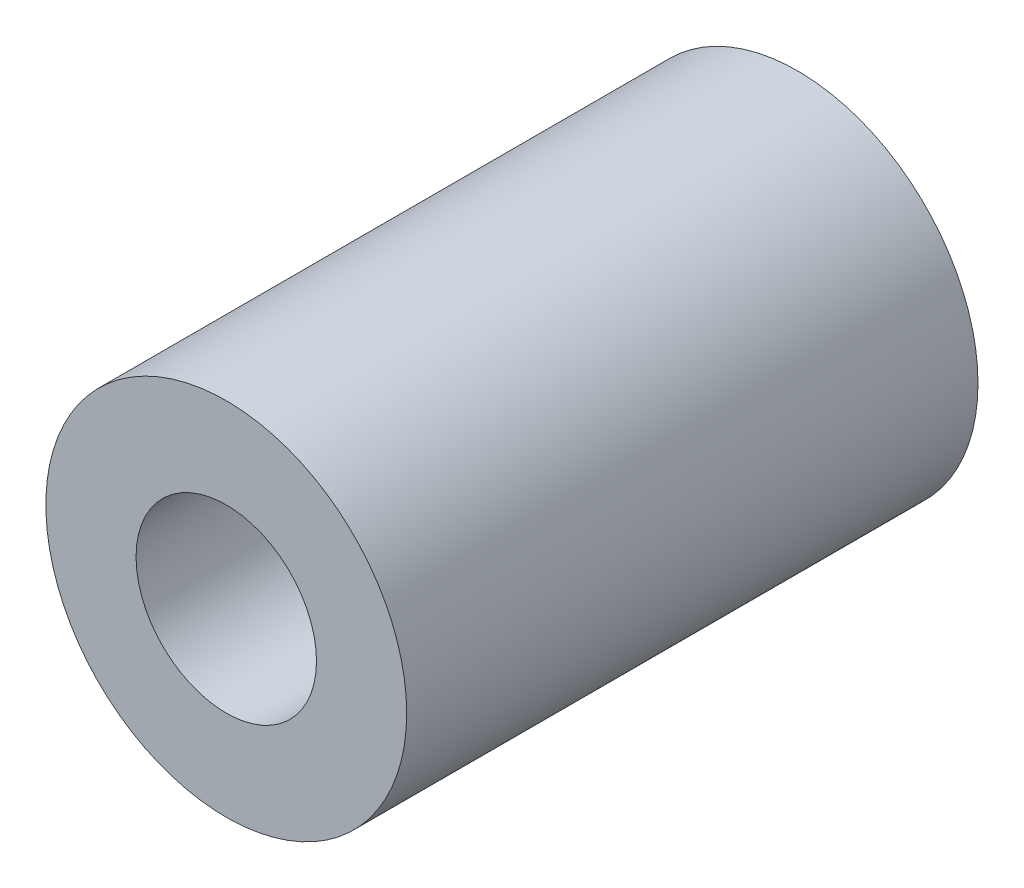
SolidWorks part; units mm, degrees
ref_plane "Front Plane" through (0, 0, 0) normal (0, 0, 1) x (1, 0, 0)
ref_plane "Top Plane" through (0, 0, 0) normal (0, 1, 0) x (1, 0, 0)
ref_plane "Right Plane" through (0, 0, 0) normal (1, 0, 0) x (0, 0, -1)
sketch "Sketch2" plane through (0, 0, 0) normal (0, 0, 1) x (1, 0, 0)
  circle A0 centre (0, 0) radius 3
  circle A1 centre (0, 0) radius 6
  dimension "D1" = 6
  dimension "D2" = 12
extrude "Boss-Extrude1" add sketch "Sketch2" along normal mid plane 19
